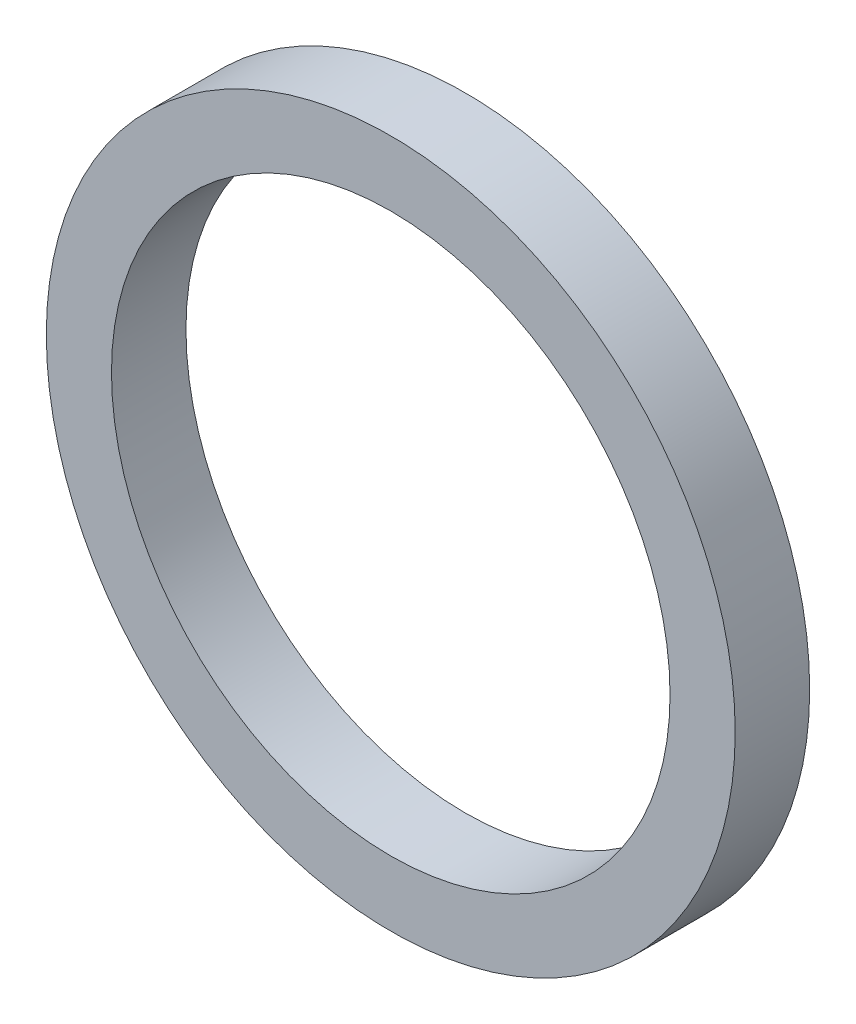
SolidWorks part; units mm, degrees
ref_plane "前视基准面" through (0, 0, 0) normal (0, 0, 1) x (1, 0, 0)
ref_plane "上视基准面" through (0, 0, 0) normal (0, 1, 0) x (1, 0, 0)
ref_plane "右视基准面" through (0, 0, 0) normal (1, 0, 0) x (0, 0, -1)
sketch "草图1" plane through (0, 0, 0) normal (0, 0, 1) x (1, 0, 0)
  circle A0 centre (0, 0) radius 18.5
  circle A1 centre (0, 0) radius 15
  dimension "D1" = 37
  dimension "D2" = 30
extrude "凸台-拉伸1" add sketch "草图1" along normal blind 4 contours A0
